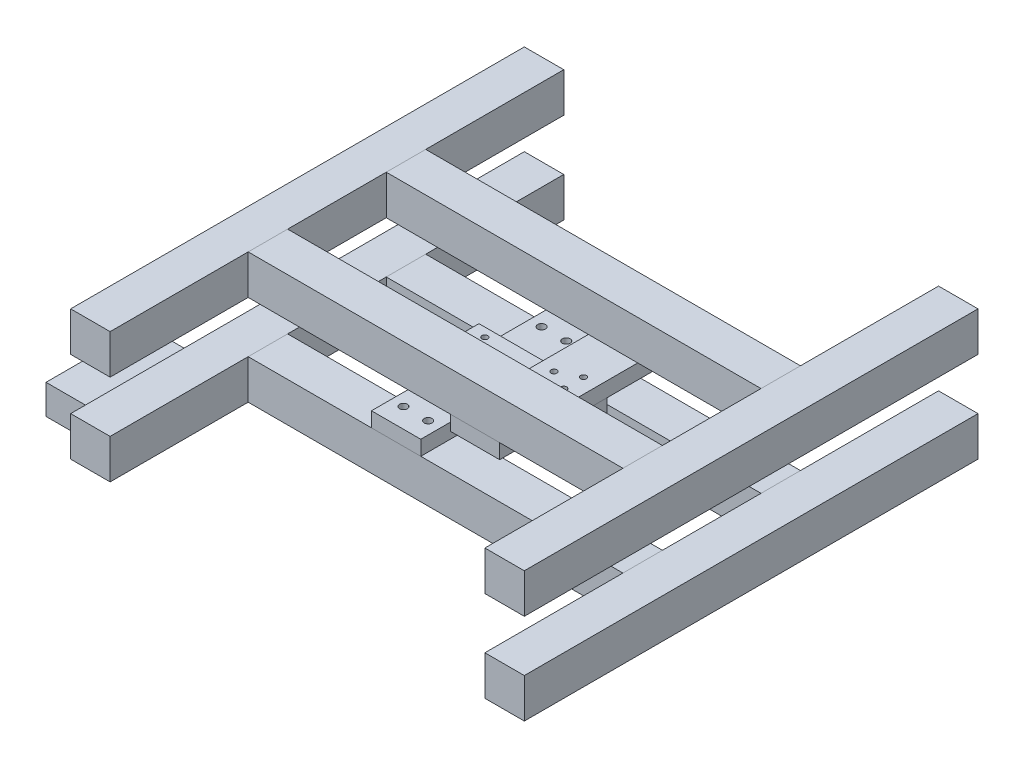
SolidWorks part; units mm, degrees
other "Camera1"
ref_plane "Front Plane" through (0, 0, 0) normal (0, 0, 1) x (1, 0, 0)
ref_plane "Top Plane" through (0, 0, 0) normal (0, 1, 0) x (1, 0, 0)
ref_plane "Right Plane" through (0, 0, 0) normal (1, 0, 0) x (0, 0, -1)
sketch "Sketch1" plane through (0, 0, 0) normal (0, 0, 1) x (1, 0, 0)
  line L1 (0, 0) -> (40, 0)
  line L2 (0, 0) -> (0, 40)
  line L3 (0, 40) -> (40, 40)
  line L4 (40, 0) -> (40, 40)
  dimension "D1" = 40
  dimension "D2" = 40
extrude "Boss-Extrude1" add sketch "Sketch1" along normal blind 460
sketch "Sketch2" plane through (40, 0, 0) normal (1, 0, 0) x (0, 0, -1)
  line L0 (-460, 0) -> (0, 0) construction
  line L1 (-320, 0) -> (-280, 0)
  line L2 (-320, 0) -> (-320, 40)
  line L3 (-320, 40) -> (-280, 40)
  line L4 (-280, 0) -> (-280, 40)
  line L5 (-460, 40) -> (0, 40) construction
  line L6 (-280, 0) -> (-180, 0)
  line L7 (-180, 0) -> (-140, 0)
  line L8 (-180, 0) -> (-180, 40)
  line L9 (-180, 40) -> (-140, 40)
  line L10 (-140, 0) -> (-140, 40)
  line L11 (0, 0) -> (0, 40) construction
  point P12 (-230, 0)
  line M6 (0, 40) -> (-460, 40)
  line M8 (-460, 0) -> (0, 0)
  dimension "D1" = 40
  dimension "D2" = 40
  dimension "D3" = 100
  dimension "D4" = 230
extrude "Boss-Extrude2" add sketch "Sketch2" along normal blind 380 separate body contours L4 L2 M8 M6 | L10 L8 M8 M6
sketch "Sketch3" plane through (0, 0, 0) normal (0, 0, 1) x (1, 0, 0)
  line L1 (420, 0) -> (460, 0)
  line L2 (420, 0) -> (420, 40)
  line L3 (420, 40) -> (460, 40)
  line L4 (460, 0) -> (460, 40)
  dimension "D1" = 40
extrude "Boss-Extrude3" add sketch "Sketch3" along normal blind 460 separate body
sketch "Sketch4" plane through (0, 40, 0) normal (0, 1, 0) x (1, 0, 0)
  line L0 (420, -140) -> (40, -140) construction
  line L1 (165, -140) -> (215, -140)
  line L2 (165, -140) -> (165, -320)
  line L3 (165, -320) -> (215, -320)
  line L4 (215, -140) -> (215, -320)
  line L5 (420, -320) -> (40, -320) construction
  line L6 (0, -22) -> (0, 22) construction
  line L9 (165, -230) -> (215, -230) construction
  circle A0 centre (177.5, -160) radius 4
  circle A1 centre (202.5, -160) radius 4
  circle A2 centre (202.5, -300) radius 4
  circle A3 centre (177.5, -300) radius 4
  circle A4 centre (180, -220) radius 3
  circle A5 centre (180, -240) radius 3
  circle A6 centre (200, -230) radius 3
  dimension "D3" = 8
  dimension "D4" = 8
  dimension "D9" = 6
  dimension "D10" = 6
  dimension "D11" = 6
  dimension "D1" = 50
  dimension "D2" = 165
  dimension "D5" = 25
  dimension "D6" = 12.5
  dimension "D7" = 20
  dimension "D8" = 20
  dimension "D12" = 10
  dimension "D13" = 10
  dimension "D14" = 15
  dimension "D15" = 15
  dimension "D16" = 15
extrude "Boss-Extrude4" add sketch "Sketch4" along normal blind 15 separate body contours A2 | L9 A6 | A6 L9 | A4 | A0 | A1 | L2 L1 L4 L3 | A3 | A5
sketch "Sketch5" plane through (165, 0, 0) normal (-1, 0, 0) x (0, 0, 1)
  line L0 (140, 55) -> (320, 55) construction
  line L1 (211, 55) -> (249, 55)
  line L2 (211, 55) -> (211, 77)
  line L3 (211, 77) -> (249, 77)
  line L4 (249, 55) -> (249, 77)
  line L5 (140, 55) -> (140, 40) construction
  point P6 (230, 55)
  dimension "D1" = 38
  dimension "D2" = 22
  dimension "D3" = 90
extrude "Boss-Extrude5" add sketch "Sketch5" against normal blind 130 separate body
sketch "Sketch6" plane through (0, 77, 0) normal (0, 1, 0) x (1, 0, 0)
  line L0 (295, -211) -> (165, -211) construction
  line L1 (295, -249) -> (295, -211) construction
  line L2 (295, -249) -> (165, -249) construction
  line L5 (230, -211) -> (230, -249) construction
  circle A3 centre (280, -240) radius 3
  circle A4 centre (260, -230) radius 3
  circle A5 centre (280, -220) radius 3
  circle A6 centre (180, -240) radius 3
  circle A7 centre (180, -220) radius 3
  circle A8 centre (200, -230) radius 3
  dimension "D1" = 6
  dimension "D2" = 6
  dimension "D3" = 6
  dimension "D4" = 20
  dimension "D5" = 9
  dimension "D6" = 15
  dimension "D7" = 9
  dimension "D8" = 35
  dimension "D9" = 19
extrude "Cut-Extrude1" cut sketch "Sketch6" against normal up to next (22 mm away)
sketch "Sketch7" plane through (0, 77, 0) normal (0, 1, 0) x (1, 0, 0)
  line L0 (420, -140) -> (40, -140) construction
  line L1 (245, -140) -> (295, -140)
  line L2 (245, -140) -> (245, -320)
  line L3 (245, -320) -> (295, -320)
  line L4 (295, -140) -> (295, -320)
  line L5 (420, -320) -> (40, -320) construction
  line L6 (295, -249) -> (295, -211) construction
  line L7 (245, -230) -> (295, -230) construction
  circle A0 centre (260, -230) radius 3
  circle A1 centre (280, -220) radius 3
  circle A2 centre (280, -240) radius 3
  circle A3 centre (257.5, -160) radius 4
  circle A4 centre (282.5, -160) radius 4
  circle A5 centre (282.5, -300) radius 4
  circle A6 centre (257.5, -300) radius 4
  dimension "D3" = 6
  dimension "D4" = 6
  dimension "D5" = 6
  dimension "D6" = 8
  dimension "D7" = 8
  dimension "D1" = 50
  dimension "D2" = 0
  dimension "D8" = 25
  dimension "D9" = 20
  dimension "D10" = 12.5
  dimension "D11" = 20
extrude "Boss-Extrude6" add sketch "Sketch7" along normal blind 15 separate body
sketch "Sketch8" plane through (0, 0, 0) normal (0, 0, 1) x (1, 0, 0)
  line L0 (420, 92) -> (460, 92)
  line L1 (460, 92) -> (460, 132)
  line L2 (460, 132) -> (420, 132)
  line L3 (420, 132) -> (420, 92)
  line L4 (295, 92) -> (295, 77) construction
  line L5 (460, 40) -> (420, 40) construction
  line L6 (0, -50.6) -> (0, 50.6) construction
  line L7 (40, 92) -> (0, 92)
  line L8 (40, 92) -> (40, 132)
  line L9 (40, 132) -> (0, 132)
  line L10 (0, 92) -> (0, 132)
  line L11 (40, 40) -> (0, 40) construction
  dimension "D1" = 40
  dimension "D2" = 40
  dimension "D3" = 125
  dimension "D4" = 52
  dimension "D5" = 40
  dimension "D6" = 52
extrude "Boss-Extrude7" add sketch "Sketch8" along normal blind 460 separate body
sketch "Sketch9" plane through (0, 132, 0) normal (0, 1, 0) x (1, 0, 0)
  line L1 (40, -140) -> (420, -140)
  line L2 (40, -140) -> (40, -180)
  line L3 (40, -180) -> (420, -180)
  line L4 (420, -140) -> (420, -180)
  line L5 (420, -280) -> (40, -280)
  line L6 (420, -280) -> (420, -320)
  line L7 (420, -320) -> (40, -320)
  line L8 (40, -280) -> (40, -320)
extrude "Boss-Extrude8" add sketch "Sketch9" against normal blind 40 separate body
sketch "Sketch11" plane through (0, 0, 0) normal (0, -1, 0) x (-1, 0, 0)
  line L0 (0, -460) -> (0, 0) construction
  line L1 (0, -435) -> (50, -435)
  line L2 (0, -435) -> (0, -335)
  line L3 (0, -335) -> (50, -335)
  line L4 (50, -435) -> (50, -335)
  line L5 (0, -460) -> (-40, -460) construction
  dimension "D1" = 100
  dimension "D2" = 50
  dimension "D3" = 25
extrude "Boss-Extrude10" add sketch "Sketch11" against normal blind 30 separate body
